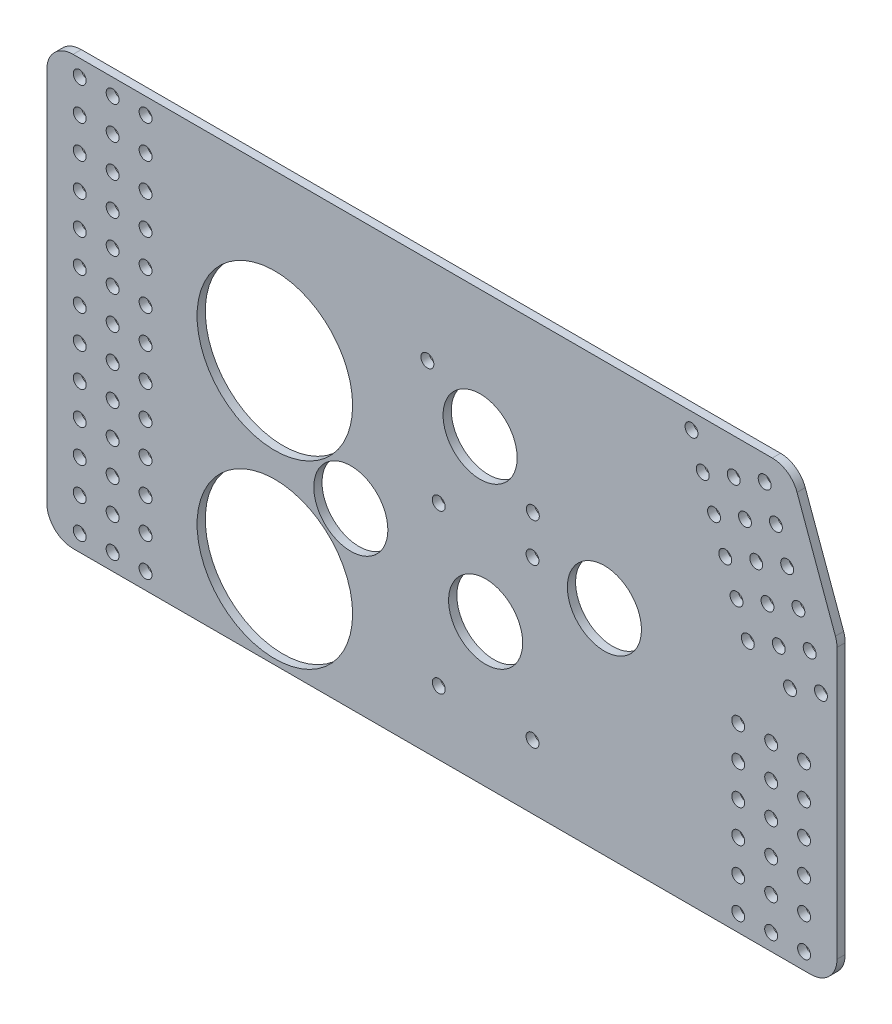
SolidWorks part; units mm, degrees
ref_plane "Front Plane" through (0, 0, 0) normal (0, 0, 1) x (1, 0, 0)
ref_plane "Top Plane" through (0, 0, 0) normal (0, 1, 0) x (1, 0, 0)
ref_plane "Right Plane" through (0, 0, 0) normal (1, 0, 0) x (0, 0, -1)
sketch "Sketch1" plane through (0, 0, 0) normal (0, 0, 1) x (1, 0, 0)
  line B0 (-152.4, 0) -> (152.4, 0)
  line B1 (152.4, 0) -> (152.4, 116.0843)
  line B2 (152.4, 116.0843) -> (134.5597, 165.1)
  line B3 (134.5597, 165.1) -> (-152.4, 165.1)
  line B4 (-152.4, 165.1) -> (-152.4, 0)
  circle B5 centre (-139.7, 158.75) radius 2.4892
  circle B6 centre (96.278, 158.8812) radius 2.4892
  circle B7 centre (112.5558, 151.2907) radius 2.4892
  circle B8 centre (124.4899, 155.6344) radius 2.4892
  circle B9 centre (114.3, 69.85) radius 2.4892
  circle B10 centre (127, 69.85) radius 2.4892
  circle B11 centre (139.7, 69.85) radius 2.4892
  circle B12 centre (100.6217, 146.9471) radius 2.4892
  circle B13 centre (116.8994, 139.3566) radius 2.4892
  circle B14 centre (128.8335, 143.7003) radius 2.4892
  circle B15 centre (104.9653, 135.013) radius 2.4892
  circle B16 centre (121.2431, 127.4226) radius 2.4892
  circle B17 centre (133.1772, 131.7662) radius 2.4892
  circle B18 centre (109.309, 123.0789) radius 2.4892
  circle B19 centre (125.5867, 115.4885) radius 2.4892
  circle B20 centre (137.5208, 119.8321) radius 2.4892
  circle B21 centre (113.6526, 111.1448) radius 2.4892
  circle B22 centre (129.9304, 103.5544) radius 2.4892
  circle B23 centre (141.8645, 107.898) radius 2.4892
  circle B24 centre (117.9963, 99.2107) radius 2.4892
  circle B25 centre (134.274, 91.6203) radius 2.4892
  circle B26 centre (146.2081, 95.9639) radius 2.4892
  circle B27 centre (114.3, 57.15) radius 2.4892
  circle B28 centre (127, 57.15) radius 2.4892
  circle B29 centre (139.7, 57.15) radius 2.4892
  circle B30 centre (114.3, 44.45) radius 2.4892
  circle B31 centre (127, 44.45) radius 2.4892
  circle B32 centre (139.7, 44.45) radius 2.4892
  circle B33 centre (114.3, 31.75) radius 2.4892
  circle B34 centre (127, 31.75) radius 2.4892
  circle B35 centre (139.7, 31.75) radius 2.4892
  circle B36 centre (114.3, 19.05) radius 2.4892
  circle B37 centre (127, 19.05) radius 2.4892
  circle B38 centre (139.7, 19.05) radius 2.4892
  circle B39 centre (114.3, 6.35) radius 2.4892
  circle B40 centre (127, 6.35) radius 2.4892
  circle B41 centre (139.7, 6.35) radius 2.4892
  circle B42 centre (-127, 158.75) radius 2.4892
  circle B43 centre (-114.3, 158.75) radius 2.4892
  circle B44 centre (-127, 146.05) radius 2.4892
  circle B45 centre (-114.3, 146.05) radius 2.4892
  circle B46 centre (-127, 133.35) radius 2.4892
  circle B47 centre (-114.3, 133.35) radius 2.4892
  circle B48 centre (-127, 120.65) radius 2.4892
  circle B49 centre (-114.3, 120.65) radius 2.4892
  circle B50 centre (-127, 107.95) radius 2.4892
  circle B51 centre (-114.3, 107.95) radius 2.4892
  circle B52 centre (-127, 95.25) radius 2.4892
  circle B53 centre (-114.3, 95.25) radius 2.4892
  circle B54 centre (-127, 82.55) radius 2.4892
  circle B55 centre (-114.3, 82.55) radius 2.4892
  circle B56 centre (-127, 69.85) radius 2.4892
  circle B57 centre (-114.3, 69.85) radius 2.4892
  circle B58 centre (-127, 57.15) radius 2.4892
  circle B59 centre (-114.3, 57.15) radius 2.4892
  circle B60 centre (-127, 44.45) radius 2.4892
  circle B61 centre (-114.3, 44.45) radius 2.4892
  circle B62 centre (-127, 31.75) radius 2.4892
  circle B63 centre (-114.3, 31.75) radius 2.4892
  circle B64 centre (-127, 19.05) radius 2.4892
  circle B65 centre (-114.3, 19.05) radius 2.4892
  circle B66 centre (-127, 6.35) radius 2.4892
  circle B67 centre (-114.3, 6.35) radius 2.4892
  circle B68 centre (-139.7, 146.05) radius 2.4892
  circle B69 centre (-139.7, 133.35) radius 2.4892
  circle B70 centre (-139.7, 120.65) radius 2.4892
  circle B71 centre (-139.7, 107.95) radius 2.4892
  circle B72 centre (-139.7, 95.25) radius 2.4892
  circle B73 centre (-139.7, 82.55) radius 2.4892
  circle B74 centre (-139.7, 69.85) radius 2.4892
  circle B75 centre (-139.7, 57.15) radius 2.4892
  circle B76 centre (-139.7, 44.45) radius 2.4892
  circle B77 centre (-139.7, 31.75) radius 2.4892
  circle B78 centre (-139.7, 19.05) radius 2.4892
  circle B79 centre (-139.7, 6.35) radius 2.4892
  circle B80 centre (14.7476, 115.9152) radius 14.2875
  circle B81 centre (-35.1245, 66.9374) radius 14.2875
  circle B82 centre (16.8723, 55.1779) radius 14.2875
  circle B83 centre (62.6832, 82.5004) radius 14.2875
  circle B84 centre (-64.4332, 101.6647) radius 29.9974
  circle B85 centre (-64.4332, 32.0687) radius 29.9974
  circle B86 centre (-5.5914, 131.1298) radius 2.4892
  circle B87 centre (35.0866, 100.7006) radius 2.4892
  circle B88 centre (-1.2125, 24.6471) radius 2.4892
  circle B89 centre (34.9571, 24.6471) radius 2.4892
  circle B90 centre (34.9571, 85.7087) radius 2.4892
  circle B91 centre (-1.2125, 85.7087) radius 2.4892
sketch_block_instance "Block-OutsidePlateBLK-1"
sketch_block "Block-OutsidePlateBLK" parameters "D1"=4.9784, "D3"=4.9784, "D4"=4.9784, "D5"=4.9784, "D6"=4.9784, "D7"=4.9784, "D8"=4.9784, "D15"=28.575, "D16"=28.575, "D17"=28.575, "D18"=28.575, "D19"=59.9948, "D20"=59.9948, "D21"=4.9784, "D22"=4.9784, "D23"=4.9784, "D24"=4.9784, "D25"=4.9784, "D26"=4.9784, "D2"=6.35, "D9"=12.7, "D10"=12.7, "D11"=12.7, "D12"=12.7, "D13"=165.1, "D14"=6.35, "D27"=18.0848, "D28"=30.5308, "D29"=18.0848, "D30"=30.5308
extrude "Boss-Extrude1" add sketch "Sketch1" along normal blind 3.175
fillet "Fillet1" radius 10.16 5 edges at (152.4, 0, 1.5875) (152.4, 116.0843, 1.5875) (134.5597, 165.1, 1.5875) (-152.4, 0, 1.5875) (-152.4, 165.1, 1.5875)
